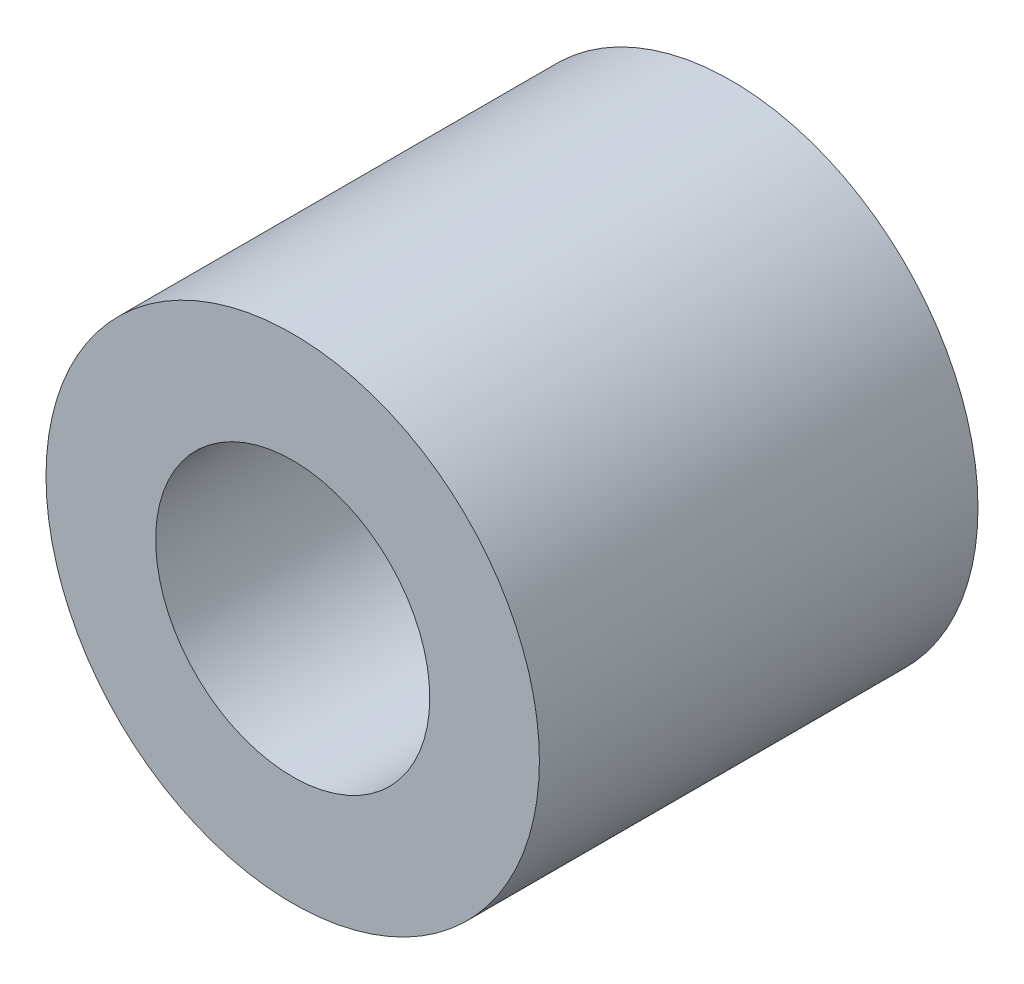
SolidWorks part; units mm, degrees
ref_plane "前视基准面" through (0, 0, 0) normal (0, 0, 1) x (1, 0, 0)
ref_plane "上视基准面" through (0, 0, 0) normal (0, 1, 0) x (1, 0, 0)
ref_plane "右视基准面" through (0, 0, 0) normal (1, 0, 0) x (0, 0, -1)
other "Configuration Table"
sketch "草图2" plane through (0, 0, 0) normal (0, 0, 1) x (1, 0, 0)
  circle A0 centre (0, 0) radius 5
  circle A1 centre (0, 0) radius 9
  dimension "D1" = 10
  dimension "D2" = 18
extrude "凸台-拉伸1" add sketch "草图2" along normal blind 16
